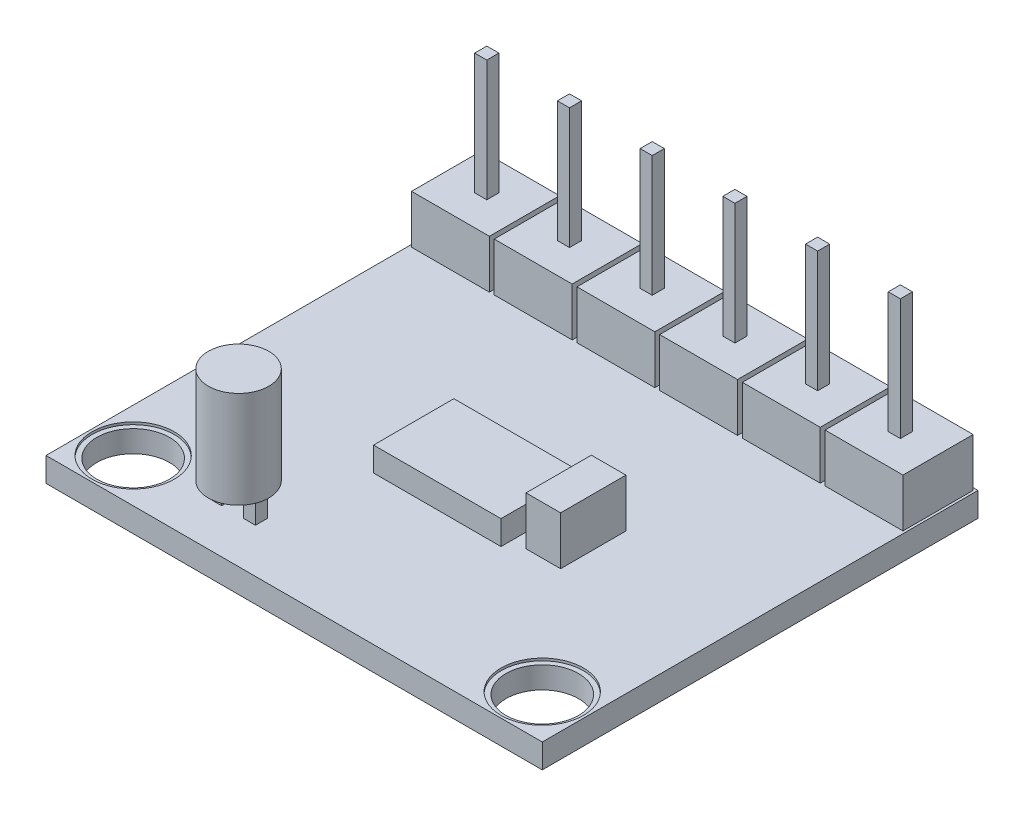
SolidWorks part; units mm, degrees
ref_plane "정면" through (0, 0, 0) normal (0, 0, 1) x (1, 0, 0)
ref_plane "윗면" through (0, 0, 0) normal (0, 1, 0) x (1, 0, 0)
ref_plane "우측면" through (0, 0, 0) normal (1, 0, 0) x (0, 0, -1)
sketch "스케치1" plane through (0, 0, 0) normal (0, 1, 0) x (1, 0, 0)
  line L1 (-10.25, 9) -> (10.25, 9)
  line L2 (-10.25, 9) -> (-10.25, -9)
  line L3 (-10.25, -9) -> (10.25, -9)
  line L4 (10.25, 9) -> (10.25, -9)
  line L5 (-10.25, 9) -> (10.25, -9) construction
  line L6 (-10.25, -9) -> (10.25, 9) construction
  point P0 (0, 0)
  dimension "D1" = 20.5
  dimension "D2" = 18
extrude "보스-돌출1" add sketch "스케치1" along normal blind 1
sketch "스케치2" plane through (0, 1, 0) normal (0, 1, 0) x (1, 0, 0)
  line L1 (-10.15, 9) -> (-6.9333, 9)
  line L3 (-10.15, 6) -> (-6.9333, 6)
  line L5 (-3.3167, 6) -> (-3.3167, 9)
  line L6 (0.1, 6) -> (0.1, 9)
  line L7 (3.5167, 6) -> (3.5167, 9)
  line L8 (-6.7333, 6) -> (-3.5167, 6)
  line L9 (6.9333, 6) -> (6.9333, 9)
  line L10 (-10.15, 9) -> (-10.15, 6)
  line L11 (-6.7333, 6) -> (-6.7333, 9)
  line L12 (-6.9333, 6) -> (-6.9333, 9)
  line L13 (-3.5167, 6) -> (-3.5167, 9)
  line L14 (-0.1, 6) -> (-0.1, 9)
  line L15 (3.3167, 6) -> (3.3167, 9)
  line L16 (6.7333, 6) -> (6.7333, 9)
  line L17 (-3.3167, 6) -> (-0.1, 6)
  line L18 (0.1, 6) -> (3.3167, 6)
  line L19 (3.5167, 6) -> (6.7333, 6)
  line L20 (6.9333, 6) -> (10.15, 6)
  line L21 (10.15, 9) -> (10.15, 6)
  line L22 (-10.15, 9) -> (-6.9333, 9)
  line L23 (6.9333, 9) -> (10.25, 9)
  line L24 (6.9333, 9) -> (10.15, 9)
  line L25 (3.5167, 9) -> (6.7333, 9)
  line L26 (3.5167, 9) -> (6.7333, 9)
  line L27 (0.1, 9) -> (3.3167, 9)
  line L28 (0.1, 9) -> (3.3167, 9)
  line L29 (-3.3167, 9) -> (-0.1, 9)
  line L30 (-3.3167, 9) -> (-0.1, 9)
  line L31 (-6.7333, 9) -> (-3.5167, 9)
  line L32 (-6.7333, 9) -> (-3.5167, 9)
  line M2 (10.25, 9) -> (-10.25, 9)
extrude "보스-돌출2" add sketch "스케치2" along normal blind 2 contours L3 L12 L10 M2 | L8 L13 L11 M2 | L5 L17 L14 M2 | L6 L18 L15 M2 | L7 L19 L16 M2 | L21 L9 L20 M2
sketch "스케치3" plane through (0, 3, 0) normal (0, 1, 0) x (1, 0, 0)
  line L0 (-10.15, 7.5) -> (-6.9333, 7.5) construction
  line L1 (-10.15, 9) -> (-10.15, 6) construction
  line L2 (-6.9333, 6) -> (-6.9333, 9) construction
  line L3 (-6.7333, 7.5) -> (-3.5167, 7.5) construction
  line L4 (-6.7333, 6) -> (-6.7333, 9) construction
  line L5 (-3.5167, 6) -> (-3.5167, 9) construction
  line L6 (-3.5167, 7.5) -> (-3.3167, 7.5) construction
  line L7 (-3.3167, 6) -> (-3.3167, 9) construction
  line L8 (-3.3167, 7.5) -> (-0.1, 7.5) construction
  line L9 (-0.1, 6) -> (-0.1, 9) construction
  line L10 (-0.1, 7.5) -> (0.1, 7.5) construction
  line L11 (0.1, 6) -> (0.1, 9) construction
  line L12 (0.1, 7.5) -> (3.3167, 7.5) construction
  line L13 (3.3167, 6) -> (3.3167, 9) construction
  line L14 (3.3167, 7.5) -> (3.5167, 7.5) construction
  line L15 (3.5167, 6) -> (3.5167, 9) construction
  line L16 (3.5167, 7.5) -> (6.7333, 7.5) construction
  line L17 (6.7333, 6) -> (6.7333, 9) construction
  line L18 (6.7333, 7.5) -> (6.9333, 7.5) construction
  line L19 (6.9333, 6) -> (6.9333, 9) construction
  line L20 (6.9333, 7.5) -> (10.15, 7.5) construction
  line L21 (10.15, 9) -> (10.15, 6) construction
  line L23 (-8.7917, 7.75) -> (-8.2917, 7.75)
  line L24 (-8.7917, 7.75) -> (-8.7917, 7.25)
  line L25 (-8.7917, 7.25) -> (-8.2917, 7.25)
  line L26 (-8.2917, 7.75) -> (-8.2917, 7.25)
  line L27 (-8.7917, 7.75) -> (-8.2917, 7.25) construction
  line L28 (-8.7917, 7.25) -> (-8.2917, 7.75) construction
  line L29 (-5.375, 7.75) -> (-4.875, 7.75)
  line L30 (-5.375, 7.75) -> (-5.375, 7.25)
  line L31 (-5.375, 7.25) -> (-4.875, 7.25)
  line L32 (-4.875, 7.75) -> (-4.875, 7.25)
  line L33 (-5.375, 7.75) -> (-4.875, 7.25) construction
  line L34 (-5.375, 7.25) -> (-4.875, 7.75) construction
  line L35 (-1.9583, 7.75) -> (-1.4583, 7.75)
  line L36 (-1.9583, 7.75) -> (-1.9583, 7.25)
  line L37 (-1.9583, 7.25) -> (-1.4583, 7.25)
  line L38 (-1.4583, 7.75) -> (-1.4583, 7.25)
  line L39 (-1.9583, 7.75) -> (-1.4583, 7.25) construction
  line L40 (-1.9583, 7.25) -> (-1.4583, 7.75) construction
  line L41 (1.4583, 7.75) -> (1.9583, 7.75)
  line L42 (1.4583, 7.75) -> (1.4583, 7.25)
  line L43 (1.4583, 7.25) -> (1.9583, 7.25)
  line L44 (1.9583, 7.75) -> (1.9583, 7.25)
  line L45 (1.4583, 7.75) -> (1.9583, 7.25) construction
  line L46 (1.4583, 7.25) -> (1.9583, 7.75) construction
  line L47 (4.875, 7.75) -> (5.375, 7.75)
  line L48 (4.875, 7.75) -> (4.875, 7.25)
  line L49 (4.875, 7.25) -> (5.375, 7.25)
  line L50 (5.375, 7.75) -> (5.375, 7.25)
  line L51 (4.875, 7.75) -> (5.375, 7.25) construction
  line L52 (4.875, 7.25) -> (5.375, 7.75) construction
  line L53 (8.2917, 7.75) -> (8.7917, 7.75)
  line L54 (8.2917, 7.75) -> (8.2917, 7.25)
  line L55 (8.2917, 7.25) -> (8.7917, 7.25)
  line L56 (8.7917, 7.75) -> (8.7917, 7.25)
  line L57 (8.2917, 7.75) -> (8.7917, 7.25) construction
  line L58 (8.2917, 7.25) -> (8.7917, 7.75) construction
  point P12 (-8.5417, 7.5)
  point P41 (-5.125, 7.5)
  point P46 (-1.7083, 7.5)
  point P51 (1.7083, 7.5)
  point P56 (5.125, 7.5)
  point P61 (8.5417, 7.5)
  dimension "D1" = 0.5
  dimension "D2" = 0.5
  dimension "D3" = 0.5
  dimension "D4" = 0.5
  dimension "D5" = 0.5
  dimension "D6" = 0.5
  dimension "D7" = 0.5
  dimension "D8" = 0.5
  dimension "D9" = 0.5
  dimension "D10" = 0.5
  dimension "D11" = 0.5
  dimension "D12" = 0.5
extrude "보스-돌출3" add sketch "스케치3" along normal blind 5 separate body
sketch "스케치4" plane through (0, 3, 0) normal (0, 1, 0) x (1, 0, 0)
  line L0 (10.15, 9) -> (10.15, 6) construction
  line L1 (-10.15, 9) -> (10.15, 9)
  line L2 (-10.15, 9) -> (-10.15, 8.9)
  line L3 (-10.15, 8.9) -> (10.15, 8.9)
  line L4 (10.15, 9) -> (10.15, 8.9)
  dimension "D1" = 0.1
extrude "컷-돌출1" cut sketch "스케치4" against normal blind 2
sketch "스케치5" plane through (0, 1, 0) normal (0, 1, 0) x (1, 0, 0)
  line L0 (0, -9) -> (0, 9) construction
  line L1 (-10.25, -9) -> (10.25, -9) construction
  line L2 (10.25, 9) -> (-10.25, 9) construction
  line L3 (-10.25, 9) -> (-10.25, -9) construction
  circle A0 centre (-8.45, -7.2) radius 1.5
  circle A1 centre (8.45, -7.2) radius 1.5
  dimension "D1" = 3
  dimension "D2" = 1.8
  dimension "D3" = 1.8
extrude "컷-돌출2" cut sketch "스케치5" against normal blind 22
sketch "스케치6" plane through (0, 1, 0) normal (0, 1, 0) x (1, 0, 0)
  circle A0 centre (-8.45, -7.2) radius 1.7
  circle A1 centre (8.45, -7.2) radius 1.5
  circle A2 centre (8.45, -7.2) radius 1.5
  circle A3 centre (-8.45, -7.2) radius 1.5
  circle A4 centre (-8.45, -7.2) radius 1.5
  circle A5 centre (8.45, -7.2) radius 1.7
  dimension "D1" = 0
  dimension "D2" = 0
  dimension "D3" = 0.2
extrude "컷-돌출3" cut sketch "스케치6" against normal blind 0.1
sketch "스케치7" plane through (0, 1, 0) normal (0, 1, 0) x (1, 0, 0)
  line L0 (-5.7756, -6.921) -> (-4.3756, -6.921) construction
  line L1 (-5.7756, -5.921) -> (-2.9756, -5.921)
  line L2 (-5.7756, -5.921) -> (-5.7756, -7.921)
  line L3 (-5.7756, -7.921) -> (-2.9756, -7.921)
  line L4 (-2.9756, -5.921) -> (-2.9756, -7.921)
  line L5 (-4.3756, -6.921) -> (-2.9756, -6.921) construction
  line L7 (-5.3256, -6.671) -> (-4.8256, -6.671)
  line L8 (-5.3256, -6.671) -> (-5.3256, -7.171)
  line L9 (-5.3256, -7.171) -> (-4.8256, -7.171)
  line L10 (-4.8256, -6.671) -> (-4.8256, -7.171)
  line L11 (-5.3256, -6.671) -> (-4.8256, -7.171) construction
  line L12 (-5.3256, -7.171) -> (-4.8256, -6.671) construction
  line L13 (-3.9256, -6.671) -> (-3.4256, -6.671)
  line L14 (-3.9256, -6.671) -> (-3.9256, -7.171)
  line L15 (-3.9256, -7.171) -> (-3.4256, -7.171)
  line L16 (-3.4256, -6.671) -> (-3.4256, -7.171)
  line L17 (-3.9256, -6.671) -> (-3.4256, -7.171) construction
  line L18 (-3.9256, -7.171) -> (-3.4256, -6.671) construction
  point P6 (-5.0756, -6.921)
  point P8 (-3.6756, -6.921)
  point P9 (-5.0756, -6.921)
  point P14 (-3.6756, -6.921)
  dimension "D1" = 2.8
  dimension "D2" = 2
  dimension "D3" = 0.5
  dimension "D4" = 0.5
  dimension "D5" = 0.5
  dimension "D6" = 0.5
extrude "보스-돌출4" add sketch "스케치7" along normal blind 1 separate body contours L16 L13 L14 L15 | L7 L10 L9 L8
sketch "스케치8" plane through (0, 2, 0) normal (0, 1, 0) x (1, 0, 0)
  line L0 (-5.0756, -6.921) -> (-3.6756, -6.921) construction
  circle A0 centre (-4.3756, -6.921) radius 1.25
  dimension "D1" = 2.5
extrude "보스-돌출5" add sketch "스케치8" along normal blind 4 separate body
sketch "스케치9" plane through (0, 1, 0) normal (0, 1, 0) x (1, 0, 0)
  line L1 (-2.8566, 0.4555) -> (2.4068, 0.4555)
  line L2 (-2.8566, 0.4555) -> (-2.8566, -2.8623)
  line L3 (-2.8566, -2.8623) -> (2.4068, -2.8623)
  line L4 (2.4068, 0.4555) -> (2.4068, -2.8623)
extrude "보스-돌출6" add sketch "스케치9" along normal blind 1 separate body
sketch "스케치10" plane through (0, 1, 0) normal (0, 1, 0) x (1, 0, 0)
  line L1 (3.0028, 0.2755) -> (4.4312, 0.2755)
  line L2 (3.0028, 0.2755) -> (3.0028, -2.4236)
  line L3 (3.0028, -2.4236) -> (4.4312, -2.4236)
  line L4 (4.4312, 0.2755) -> (4.4312, -2.4236)
extrude "보스-돌출7" add sketch "스케치10" along normal blind 2 separate body
